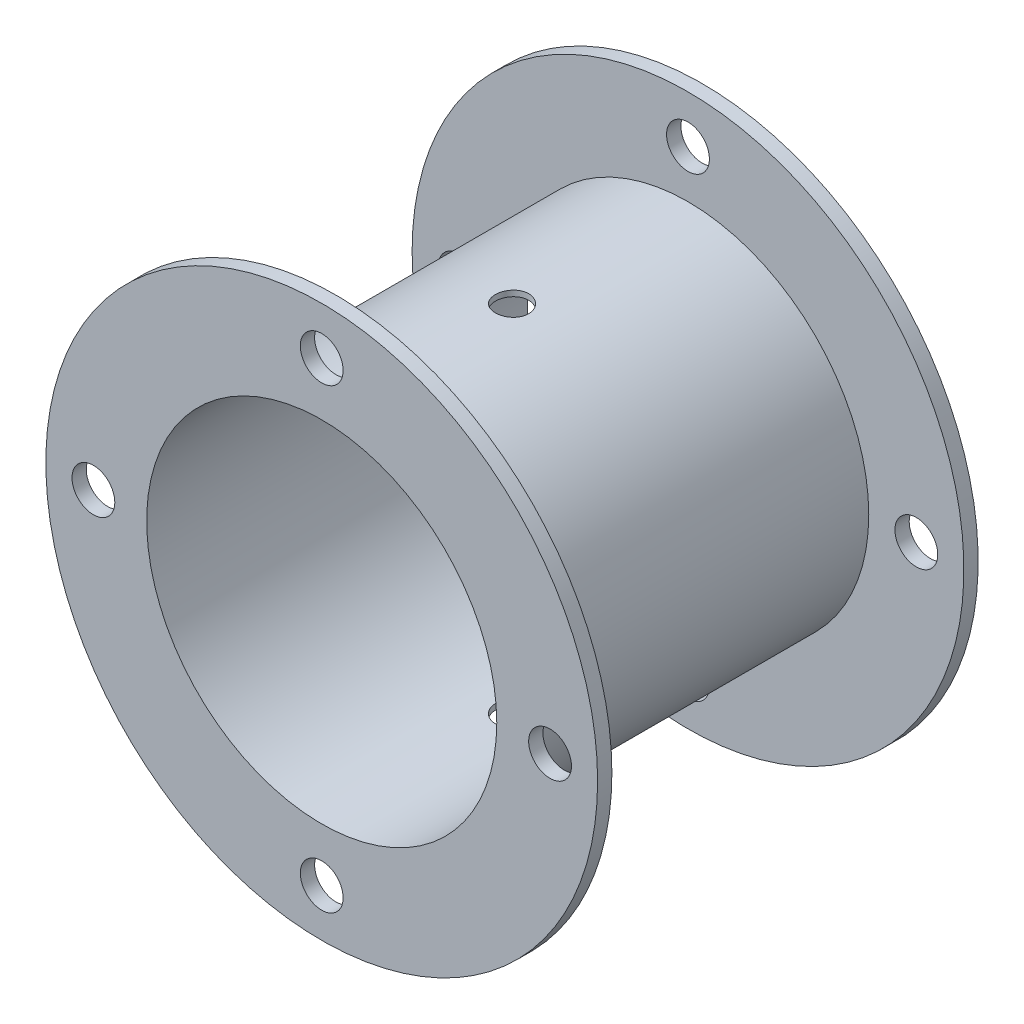
SolidWorks part; units mm, degrees
ref_plane "Front Plane" through (0, 0, 0) normal (0, 0, 1) x (1, 0, 0)
ref_plane "Top Plane" through (0, 0, 0) normal (0, 1, 0) x (1, 0, 0)
ref_plane "Right Plane" through (0, 0, 0) normal (1, 0, 0) x (0, 0, -1)
sketch "Sketch1" plane through (0, 0, 0) normal (0, 0, 1) x (1, 0, 0)
  circle A0 centre (0, 0) radius 38
  circle A1 centre (0, 0) radius 36.8
  dimension "D1" = 76
  dimension "D2" = 1.2
extrude "Boss-Extrude1" add sketch "Sketch1" along normal blind 80
sketch "Sketch2" plane through (0, 0, 0) normal (0, 1, 0) x (1, 0, 0)
  line L0 (0, 0) -> (0, -80) construction
  line L1 (-38, -80) -> (38, -80) construction
  circle A0 centre (0, -40) radius 3.5
  dimension "D1" = 7
extrude "Cut-Extrude1" cut sketch "Sketch2" against normal through all and the other way through all
sketch "Sketch3" plane through (0, 0, 80) normal (0, 0, 1) x (1, 0, 0)
  circle A0 centre (0, 0) radius 38
  circle A1 centre (0, 0) radius 58
  circle A2 centre (0, 0) radius 48 construction
  circle A3 centre (-48, 0) radius 4.5
  circle A4 centre (0, 48) radius 4.5
  circle A5 centre (48, 0) radius 4.5
  circle A6 centre (0, -48) radius 4.5
  point P18 (0, 0)
  dimension "D3" = 9
  dimension "D1" = 20
  dimension "D2" = 10
  dimension "D4" = 4
extrude "Boss-Extrude2" add sketch "Sketch3" against normal blind 3
sketch "Sketch4" plane through (0, 0, 0) normal (0, 0, -1) x (-1, 0, 0)
  circle A0 centre (0, 0) radius 38
  circle A1 centre (0, 0) radius 58
  circle A2 centre (48, 0) radius 4.5
  circle A3 centre (0, -48) radius 4.5
  circle A4 centre (-48, 0) radius 4.5
  circle A5 centre (0, 48) radius 4.5
extrude "Boss-Extrude3" add sketch "Sketch4" against normal blind 3
